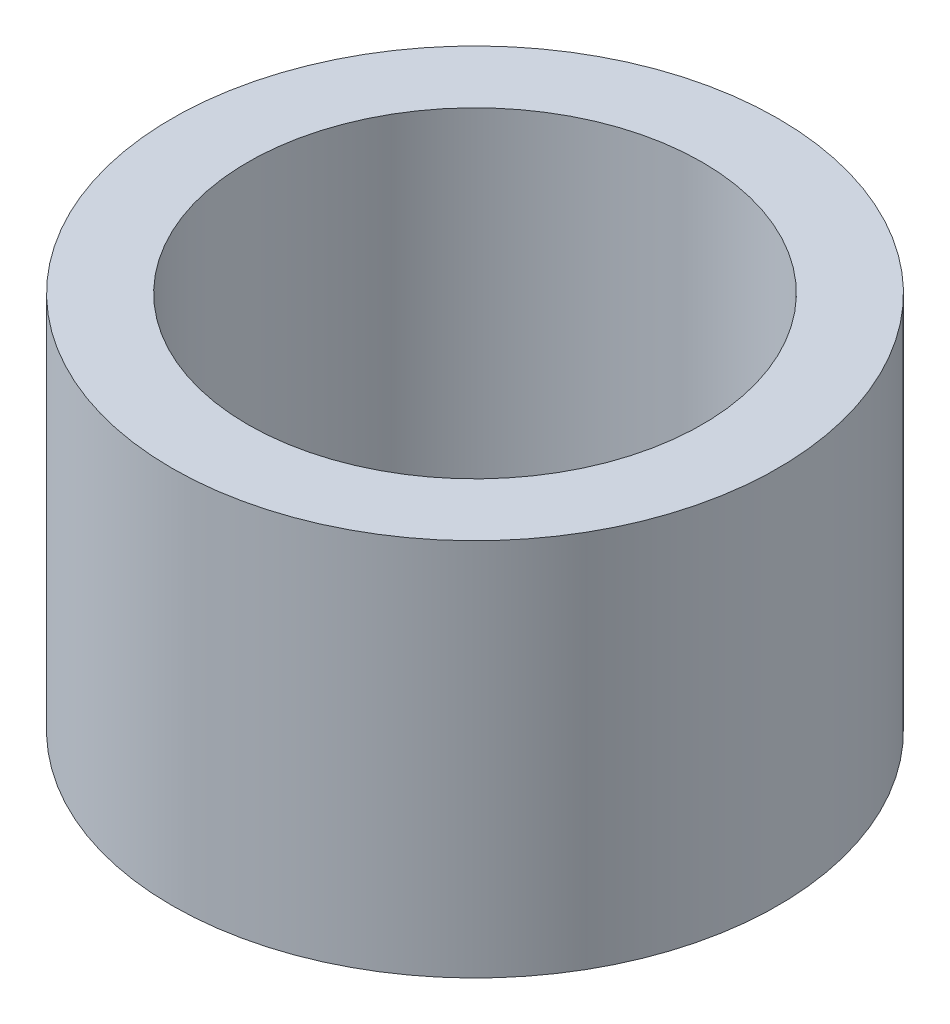
SolidWorks part; units mm, degrees
ref_plane "Front Plane" through (0, 0, 0) normal (0, 0, 1) x (1, 0, 0)
ref_plane "Top Plane" through (0, 0, 0) normal (0, 1, 0) x (1, 0, 0)
ref_plane "Right Plane" through (0, 0, 0) normal (1, 0, 0) x (0, 0, -1)
sketch "Sketch1" plane through (0, 0, 0) normal (0, 1, 0) x (1, 0, 0)
  circle A0 centre (0, 0) radius 1.5
  circle A1 centre (0, 0) radius 2
  dimension "D1" = 3
  dimension "D2" = 0.5
extrude "Boss-Extrude1" add sketch "Sketch1" along normal blind 2.5
